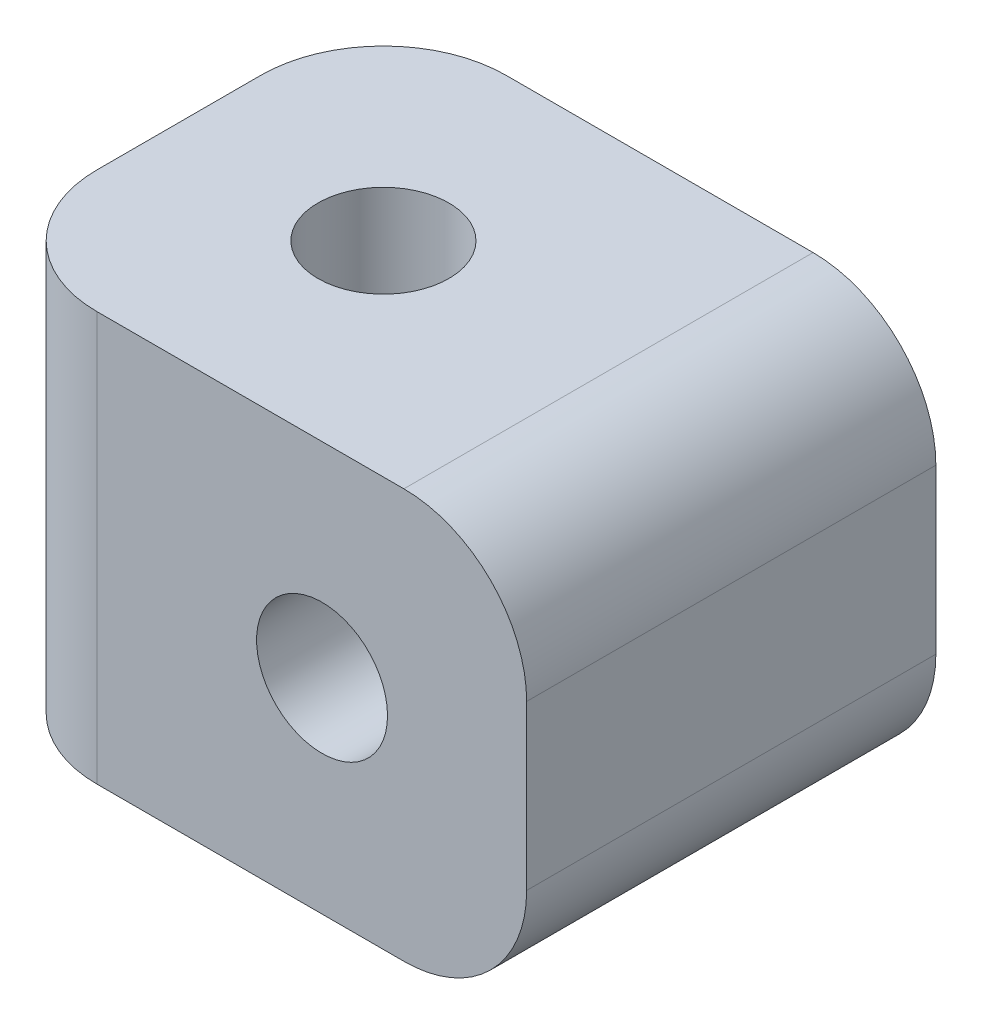
SolidWorks part; units mm, degrees
ref_plane "Front" through (0, 0, 0) normal (0, 0, 1) x (1, 0, 0)
ref_plane "Top" through (0, 0, 0) normal (0, 1, 0) x (1, 0, 0)
ref_plane "Right" through (0, 0, 0) normal (1, 0, 0) x (0, 0, -1)
sketch "Sketch1" plane through (0, 0, 0) normal (0, 1, 0) x (1, 0, 0)
  line L1 (0, 0) -> (13.5, 0)
  line L2 (0, 0) -> (0, -10)
  line L3 (0, -10) -> (13.5, -10)
  line L4 (13.5, 0) -> (13.5, -10)
  dimension "D1" = 13.5
  dimension "D2" = 10
extrude "Boss-Extrude1" add sketch "Sketch1" along normal blind 10
sketch "Sketch2" plane through (0, 0, 10) normal (0, 0, 1) x (1, 0, 0)
  line L0 (0, 0) -> (13.5, 0) construction
  line L1 (13.5, 10) -> (13.5, 0) construction
  circle A0 centre (8.5, 5) radius 1.6
  dimension "D1" = 3.2
  dimension "D2" = 5
  dimension "D3" = 5
extrude "Cut-Extrude1" cut sketch "Sketch2" against normal through all
sketch "Sketch3" plane through (0, 10, 0) normal (0, 1, 0) x (1, 0, 0)
  line L0 (0, -10) -> (13.5, -10) construction
  line L1 (0, 0) -> (0, -10) construction
  circle A0 centre (5, -5) radius 1.6
  dimension "D1" = 3.2
  dimension "D2" = 5
  dimension "D3" = 5
extrude "Cut-Extrude2" cut sketch "Sketch3" against normal through all
fillet "Fillet1" radius 3 4 edges at (0, 5, 0) (0, 5, 10) (13.5, 0, 5) (13.5, 10, 5)
